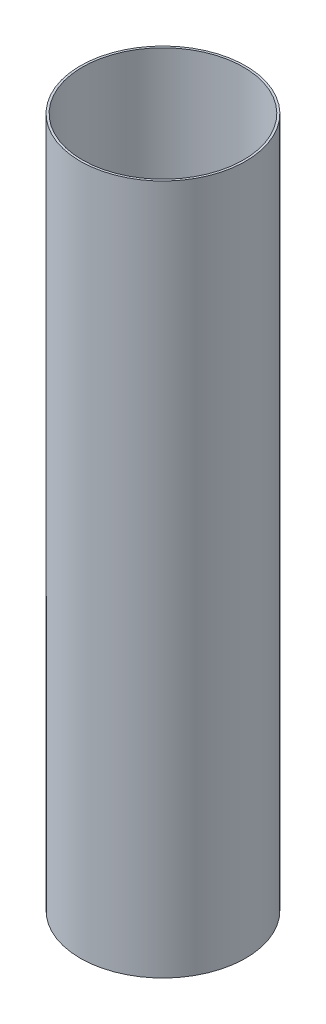
SolidWorks part; units mm, degrees
ref_plane "Front Plane" through (0, 0, 0) normal (0, 0, 1) x (1, 0, 0)
ref_plane "Top Plane" through (0, 0, 0) normal (0, 1, 0) x (1, 0, 0)
ref_plane "Right Plane" through (0, 0, 0) normal (1, 0, 0) x (0, 0, -1)
sketch "Sketch1" plane through (0, 0, 0) normal (0, 1, 0) x (1, 0, 0)
  circle A0 centre (0, 0) radius 1095.375
  circle A1 centre (0, 0) radius 1066.8
extrude "Boss-Extrude1" add sketch "Sketch1" along normal blind 9144
sketch "Sketch2" plane through (0, 0, 0) normal (0, 0, 1) x (1, 0, 0)
  line L0 (0, 9144) -> (0, 9777.4) construction
  line L1 (1066.8, 9144) -> (-1066.8, 9144) construction
  line L2 (1066.8, 9144) -> (1095.375, 9144)
  arc A0 (1095.375, 9144) -> (-389.2672, 9453.002) centre (265.9051, 8879.7826) ccw
  arc A1 (1066.8, 9144) -> (-389.2672, 9453.002) centre (252.4125, 8891.5875) ccw
